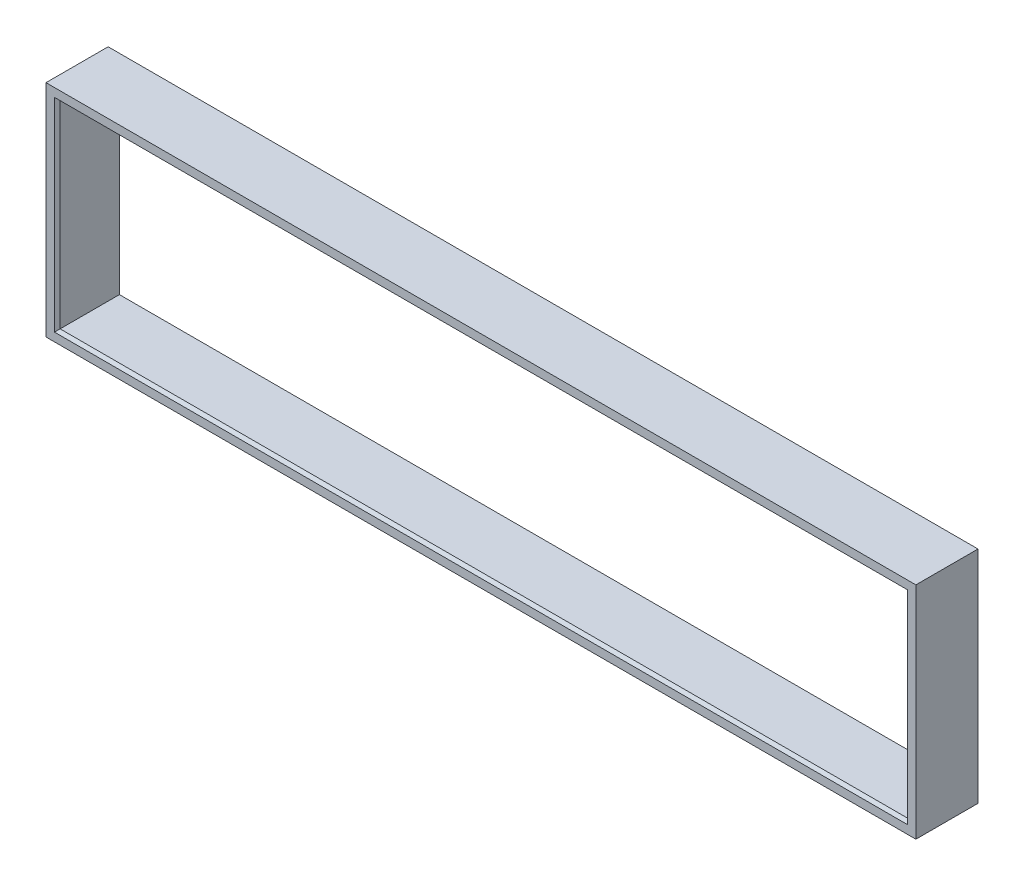
SolidWorks part; units mm, degrees
ref_plane "Спереди" through (0, 0, 0) normal (0, 0, 1) x (1, 0, 0)
ref_plane "Сверху" through (0, 0, 0) normal (0, 1, 0) x (1, 0, 0)
ref_plane "Справа" through (0, 0, 0) normal (1, 0, 0) x (0, 0, -1)
sketch "Эскиз1" plane through (0, 0, 0) normal (0, 0, 1) x (1, 0, 0)
  line L1 (-150, 35) -> (150, 35)
  line L2 (-150, 35) -> (-150, -35)
  line L3 (-150, -35) -> (150, -35)
  line L4 (150, 35) -> (150, -35)
  line L5 (-154, 39) -> (154, 39)
  line L6 (-154, 39) -> (-154, -39)
  line L7 (-154, -39) -> (154, -39)
  line L8 (154, 39) -> (154, -39)
  dimension "D1" = 4
  dimension "D2" = 4
  dimension "D3" = 4
  dimension "D4" = 4
extrude "Бобышка-Вытянуть1" add sketch "Эскиз1" along normal blind 2 and the other way blind 20
chamfer "Фаска1" distance 1 angle 45 4 edges at (-150, 0, 2) (0, -35, 2) (150, 0, 2) (0, 35, 2)
